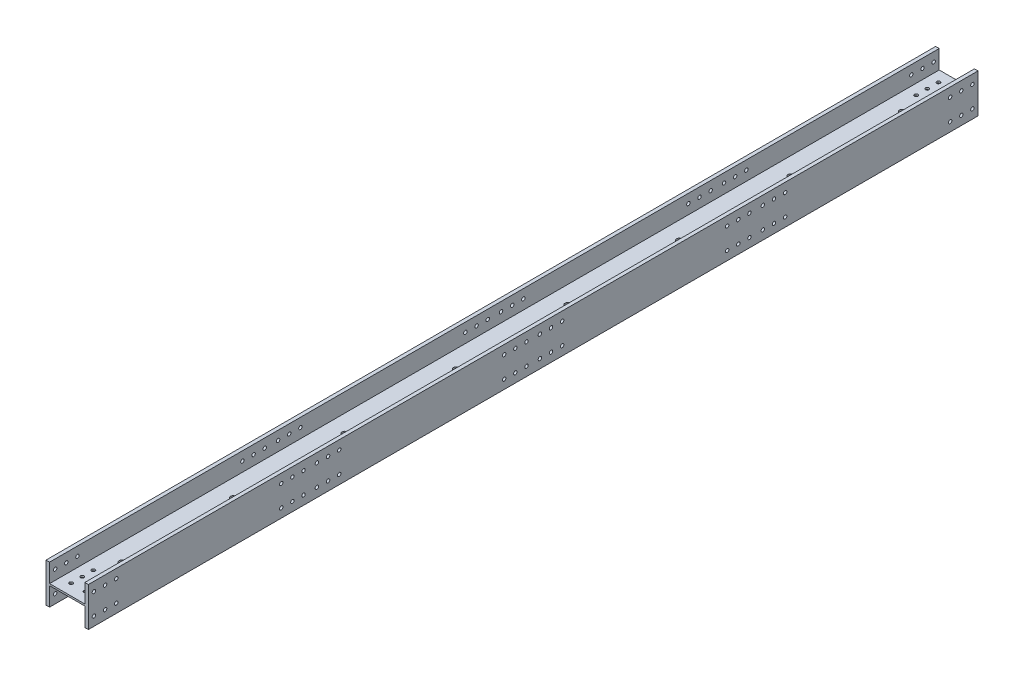
SolidWorks part; units mm, degrees
ref_plane "前视基准面" through (0, 0, 0) normal (0, 0, 1) x (1, 0, 0)
ref_plane "上视基准面" through (0, 0, 0) normal (0, 1, 0) x (1, 0, 0)
ref_plane "右视基准面" through (0, 0, 0) normal (1, 0, 0) x (0, 0, -1)
sketch "草图1" plane through (0, 0, 0) normal (0, 0, 1) x (1, 0, 0)
  line L0 (-1000, 0) -> (49000, 0) construction
  line L1 (0, -1000) -> (0, 49000) construction
  line L3 (-190, 175) -> (190, 175)
  line L4 (-190, 175) -> (-190, -175)
  line L5 (-190, -175) -> (190, -175)
  line L6 (190, 175) -> (190, -175)
  line L7 (-158, 175) -> (158, 175)
  line L8 (-158, 175) -> (-158, 8)
  line L9 (-158, 8) -> (158, 8)
  line L10 (158, 175) -> (158, 8)
  line L11 (-158, -8) -> (158, -8)
  line L12 (-158, -8) -> (-158, -175)
  line L13 (-158, -175) -> (158, -175)
  line L14 (158, -8) -> (158, -175)
  dimension "D1" = 380
  dimension "D2" = 350
  dimension "D3" = 190
  dimension "D4" = 175
  dimension "D5" = 8
  dimension "D6" = 16
  dimension "D7" = 32
  dimension "D8" = 32
extrude "拉伸1" add sketch "草图1" along normal blind 3990 contours L11 L14 L5 L6 L3 L10 L9 L8 L4 L12
sketch "草图2" plane through (190, 0, 0) normal (1, 0, 0) x (0, 0, -1)
  line L0 (-4990, 0) -> (45010, 0) construction
  line L1 (-3990, 175) -> (-3990, -175) construction
  line L2 (-3940, 95) -> (-3840, 95) construction
  line L3 (-3940, 95) -> (-3940, -95) construction
  line L4 (-3940, 95) -> (-2260, 95) construction
  line L5 (-2060, 95) -> (-1740, 95) construction
  line L6 (-1940, 95) -> (-260, 95) construction
  circle A0 centre (-3940, 95) radius 15.5
  circle A1 centre (-3840, 95) radius 15.5
  circle A2 centre (-3740, 95) radius 15.5
  circle A3 centre (-3940, -95) radius 15.5
  circle A4 centre (-3840, -95) radius 15.5
  circle A5 centre (-3740, -95) radius 15.5
  circle A6 centre (-2260, 95) radius 15.5
  circle A7 centre (-2160, 95) radius 15.5
  circle A8 centre (-2060, 95) radius 15.5
  circle A9 centre (-2260, -95) radius 15.5
  circle A10 centre (-2160, -95) radius 15.5
  circle A11 centre (-2060, -95) radius 15.5
  circle A12 centre (-1740, 95) radius 15.5
  circle A13 centre (-1940, 95) radius 15.5
  circle A14 centre (-1840, 95) radius 15.5
  circle A15 centre (-1940, -95) radius 15.5
  circle A16 centre (-1840, -95) radius 15.5
  circle A17 centre (-1740, -95) radius 15.5
  circle A18 centre (-260, 95) radius 15.5
  circle A19 centre (-60, 95) radius 15.5
  circle A20 centre (-60, -95) radius 15.5
  circle A21 centre (-160, 95) radius 15.5
  circle A22 centre (-160, -95) radius 15.5
  circle A23 centre (-260, -95) radius 15.5
  point P5 (-3990, 0)
  dimension "D1" = 31
  dimension "D2" = 50
  dimension "D3" = 95
  dimension "D4" = 100
  dimension "D5" = 100
  dimension "D6" = 190
  dimension "D7" = 1680
  dimension "D8" = 320
  dimension "D9" = 1680
extrude "拉伸2" cut sketch "草图2" against normal through all
sketch "草图3" plane through (0, 8, 0) normal (0, 1, 0) x (1, 0, 0)
  line L0 (-810, -1995) -> (49190, -1995) construction
  line L1 (190, -3990) -> (190, 0) construction
  line L2 (0, -1000) -> (0, 49000) construction
  line L4 (0, -500) -> (0, -1500) construction
  line L5 (-158, -3990) -> (158, -3990) construction
  line L6 (-65, -3890) -> (65, -3890) construction
  line L7 (-65, -3890) -> (-65, -3790) construction
  circle A0 centre (-65, -3890) radius 15.5
  circle A1 centre (65, -3890) radius 15.5
  circle A2 centre (-65, -3790) radius 15.5
  circle A3 centre (65, -3790) radius 15.5
  circle A4 centre (-65, -3690) radius 15.5
  circle A5 centre (65, -3690) radius 15.5
  circle A6 centre (0, -500) radius 25
  circle A7 centre (0, -1500) radius 25
  circle A8 centre (0, -2500) radius 25
  circle A9 centre (0, -3500) radius 25
  point P5 (190, -1995)
  dimension "D1" = 100
  dimension "D6" = 50
  dimension "D8" = 1000
  dimension "D3" = 31
  dimension "D7" = 190
  dimension "D2" = 65
  dimension "D4" = 130
  dimension "D5" = 100
extrude "拉伸3" cut sketch "草图3" against normal through all
mirror "镜向1" about plane through (0, 0, 0) normal (0, 0, 1) of bodies 103
